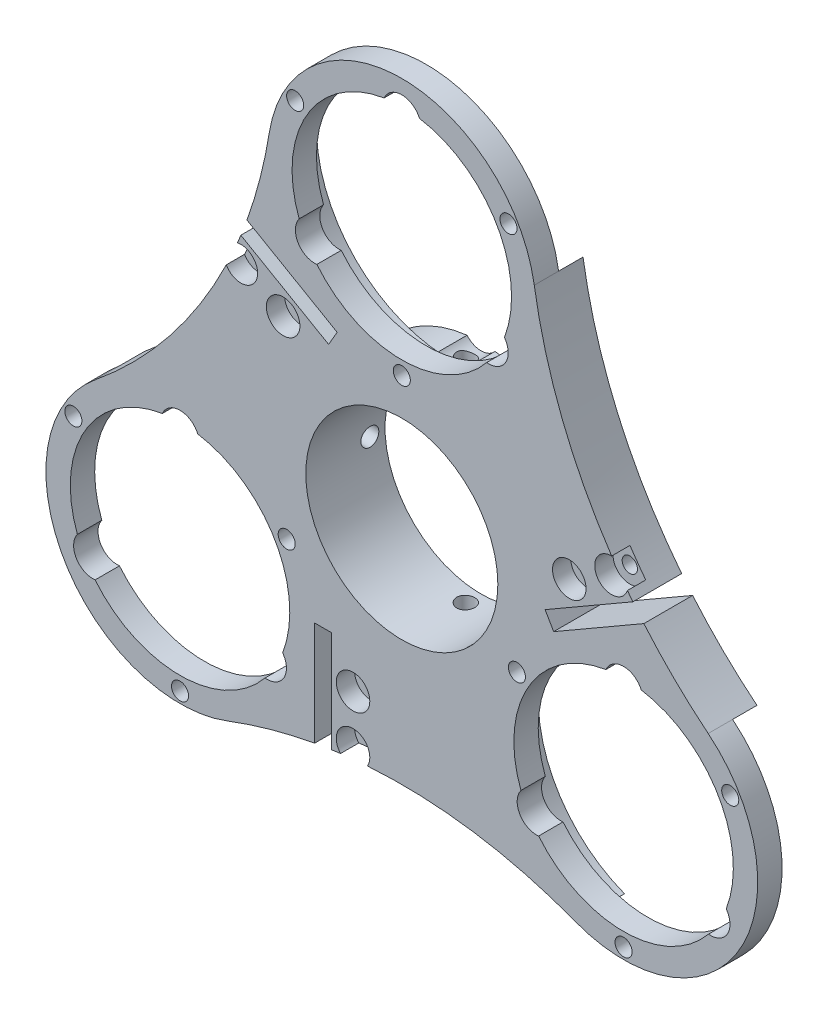
SolidWorks part; units mm, degrees
ref_plane "前视基准面" through (0, 0, 0) normal (0, 0, 1) x (1, 0, 0)
ref_plane "上视基准面" through (0, 0, 0) normal (0, 1, 0) x (1, 0, 0)
ref_plane "右视基准面" through (0, 0, 0) normal (1, 0, 0) x (0, 0, -1)
sketch "草图1" plane through (0, 0, 0) normal (0, 0, 1) x (1, 0, 0)
  circle A0 centre (0, 0) radius 15.75
  circle A1 centre (0, 0) radius 23 construction
  circle A3 centre (0, 0) radius 20
extrude "凸台-拉伸1" add sketch "草图1" along normal blind 5
sketch "草图2" plane through (0, 0, 5) normal (0, 0, 1) x (1, 0, 0)
  circle A0 centre (0, 0) radius 24 construction
  arc A2 (0, -25.8924) -> (22.4235, 12.9462) centre (20.7846, -12) ccw
  arc A3 (-22.4235, 12.9462) -> (0, -25.8924) centre (-20.7846, -12) ccw
  arc A5 (22.4235, 12.9462) -> (-22.4235, 12.9462) centre (0, 24) ccw
  point P12 (0, 0)
extrude "凸台-拉伸2" add sketch "草图2" along normal blind 8
sketch "草图3" plane through (0, 0, 13) normal (0, 0, 1) x (1, 0, 0)
  circle A0 centre (0, 42) radius 18
  circle A1 centre (36.3731, -21) radius 18
  circle A2 centre (-36.3731, -21) radius 18
  point P3 (0, 42)
  point P10 (0, 0)
  dimension "D1" = 3
  dimension "D3" = 42
extrude "凸台-拉伸3" add sketch "草图3" along normal blind 12
sketch "草图8" plane through (0, 0, 5) normal (0, 0, -1) x (-1, 0, 0)
  line L0 (0, 42) -> (36.3731, -21) construction
  line L1 (0, 0) -> (18.1865, 10.5) construction
  line L2 (18.1865, 10.5) -> (86.4245, 49.8972) construction
  line L3 (0, 0) -> (0, -8.0959) construction
  circle A0 centre (0, 0) radius 42 construction
  circle A4 centre (0, 42) radius 22
  circle A5 centre (36.3731, -21) radius 22
  circle A6 centre (-36.3731, -21) radius 22
  arc A7 (21.7226, 45.4827) -> (50.2505, -3.929) centre (100.7138, 58.1471) ccw
  arc A8 (-21.7226, 45.4827) -> (-50.2505, -3.929) centre (-100.7138, 58.1471) cw
  arc A9 (28.5279, -41.5537) -> (-28.5279, -41.5537) centre (0, -116.2943) ccw
  point P12 (0, 0)
  point P14 (0, 0)
  arc M7 (22.4235, 12.9462) -> (-22.4235, 12.9462) centre (0, 24) ccw
  arc M9 (-22.4235, 12.9462) -> (0, -25.8924) centre (-20.7846, -12) ccw
  arc M11 (0, -25.8924) -> (22.4235, 12.9462) centre (20.7846, -12) ccw
  dimension "D1" = 3
extrude "凸台-拉伸6" add sketch "草图8" against normal up to surface (8 mm away) contours A4 M7 | A7 A4 A5 M7 M11 | A5 M11 | A9 A5 A6 M11 M9 | A6 M9 | A4 A8 A6 M9 M7
sketch "草图4" plane through (0, 0, 25) normal (0, 0, 1) x (1, 0, 0)
  circle A0 centre (0, 42) radius 15
  circle A1 centre (36.3731, -21) radius 15
  circle A2 centre (-36.3731, -21) radius 15
  point P10 (0, 0)
  dimension "D1" = 3
extrude "切除-拉伸1" cut sketch "草图4" against normal blind 16
sketch "草图6" plane through (0, 0, 25) normal (0, 0, 1) x (1, 0, 0)
  arc A7 (2.6444, 56.7651) -> (-2.6444, 56.7651) centre (0, 58.5) ccw
  arc A11 (2.6444, 56.7651) -> (-2.6444, 56.7651) centre (0, 42) ccw
  arc A12 (11.4647, 32.3274) -> (14.1091, 36.9075) centre (14.2894, 33.75) ccw
  arc A13 (11.4647, 32.3274) -> (14.1091, 36.9075) centre (0, 42) ccw
  arc A14 (-14.1091, 36.9075) -> (-11.4647, 32.3274) centre (-14.2894, 33.75) ccw
  arc A15 (-14.1091, 36.9075) -> (-11.4647, 32.3274) centre (0, 42) ccw
  arc A16 (47.8378, -30.6726) -> (50.4822, -26.0925) centre (50.6625, -29.25) ccw
  arc A17 (47.8378, -30.6726) -> (50.4822, -26.0925) centre (36.3731, -21) ccw
  arc A18 (22.264, -26.0925) -> (24.9083, -30.6726) centre (22.0836, -29.25) ccw
  arc A19 (22.264, -26.0925) -> (24.9083, -30.6726) centre (36.3731, -21) ccw
  arc A20 (39.0174, -6.2349) -> (33.7287, -6.2349) centre (36.3731, -4.5) ccw
  arc A21 (39.0174, -6.2349) -> (33.7287, -6.2349) centre (36.3731, -21) ccw
  arc A22 (-50.4822, -26.0925) -> (-47.8378, -30.6726) centre (-50.6625, -29.25) ccw
  arc A23 (-50.4822, -26.0925) -> (-47.8378, -30.6726) centre (-36.3731, -21) ccw
  arc A24 (-33.7287, -6.2349) -> (-39.0174, -6.2349) centre (-36.3731, -4.5) ccw
  arc A25 (-33.7287, -6.2349) -> (-39.0174, -6.2349) centre (-36.3731, -21) ccw
  arc A26 (-24.9083, -30.6726) -> (-22.264, -26.0925) centre (-22.0836, -29.25) ccw
  arc A27 (-24.9083, -30.6726) -> (-22.264, -26.0925) centre (-36.3731, -21) ccw
  point P14 (0, 42)
  point P25 (36.3731, -21)
  point P37 (-36.3731, -21)
  point P38 (0, 0)
  dimension "D1" = 3
  dimension "D2" = 16.5
sketch "草图7" plane through (0, 0, 9) normal (0, 0, 1) x (1, 0, 0)
  circle A0 centre (0, 42) radius 2
  circle A1 centre (36.3731, -21) radius 2
  circle A2 centre (-36.3731, -21) radius 2
  point P3 (36.3731, -21)
  point P9 (0, 0)
  dimension "D1" = 3
extrude "切除-拉伸2" cut sketch "草图7" against normal blind 10
extrude "凸台-拉伸7" add sketch "草图6" against normal up to next
sketch "草图9" plane through (0, 0, 25) normal (0, 0, 1) x (1, 0, 0)
  circle A0 centre (0, 42) radius 17 construction
  circle A1 centre (0, 59) radius 1.475
  circle A2 centre (14.7224, 33.5) radius 1.475
  circle A3 centre (-14.7224, 33.5) radius 1.475
  circle A4 centre (51.0955, -29.5) radius 1.475
  circle A5 centre (21.6506, -29.5) radius 1.475
  circle A6 centre (36.3731, -4) radius 1.475
  circle A7 centre (36.3731, -21) radius 17 construction
  circle A8 centre (-51.0955, -29.5) radius 1.475
  circle A9 centre (-36.3731, -4) radius 1.475
  circle A10 centre (-21.6506, -29.5) radius 1.475
  circle A11 centre (-36.3731, -21) radius 17 construction
  point P12 (0, 42)
  point P21 (36.3731, -21)
  point P30 (-36.3731, -21)
  point P31 (0, 0)
  dimension "D1" = 3
  dimension "D2" = 3
ref_plane "基准面1" through (0, 0, 2.5) normal (0, 0, -1) x (-1, 0, 0)
sketch "草图10" plane through (0, 0, 2.5) normal (0, 0, -1) x (-1, 0, 0)
  line L0 (0, 26.5971) -> (0, -28.7314) construction
  line L1 (0, 23.6711) -> (1.475, 23.6711)
  line L2 (1.475, 23.6711) -> (1.475, -24.2093)
  line L3 (1.475, -24.2093) -> (0, -24.2093)
  line L4 (0, -24.2093) -> (0, 23.6711)
revolve "切除-旋转1" cut sketch "草图10" angle 360 about L0
sketch "草图11" plane through (0, 0, 2.5) normal (0, 0, -1) x (-1, 0, 0)
  line L0 (-35.3446, 0) -> (29.9106, 0) construction
  line L1 (-23.6643, 0) -> (-23.6643, 1.475)
  line L2 (-23.6643, 1.475) -> (24.1188, 1.475)
  line L3 (24.1188, 1.475) -> (24.1188, 0)
  line L4 (24.1188, 0) -> (-23.6643, 0)
revolve "切除-旋转2" cut sketch "草图11" angle 360 about L0
sketch "草图14" plane through (0, 0, 5) normal (0, 0, -1) x (-1, 0, 0)
  circle A0 centre (0, 0) radius 15.75
extrude "切除-拉伸6" cut sketch "草图14" against normal up to surface (8 mm away) up to face at (-36.3731, -21, 13)
sketch "草图16" plane through (0, 0, 13) normal (0, 0, 1) x (1, 0, 0)
  arc A0 (-2.8987, 59.7651) -> (-16.8343, 35.6278) centre (0, 42) ccw
  arc A1 (2.8987, 59.7651) -> (-2.8987, 59.7651) centre (0, 58.5) ccw
  arc A2 (13.9357, 30.6072) -> (16.8343, 35.6278) centre (14.2894, 33.75) ccw
  arc A3 (-16.8343, 35.6278) -> (-13.9357, 30.6072) centre (-14.2894, 33.75) ccw
  arc A4 (-13.9357, 30.6072) -> (13.9357, 30.6072) centre (0, 42) ccw
  arc A5 (16.8343, 35.6278) -> (2.8987, 59.7651) centre (0, 42) ccw
  arc A6 (53.2074, -27.3722) -> (39.2717, -3.2349) centre (36.3731, -21) ccw
  arc A7 (50.3087, -32.3928) -> (53.2074, -27.3722) centre (50.6625, -29.25) ccw
  arc A8 (19.5387, -27.3722) -> (22.4374, -32.3928) centre (22.0836, -29.25) ccw
  arc A9 (39.2717, -3.2349) -> (33.4744, -3.2349) centre (36.3731, -4.5) ccw
  arc A10 (33.4744, -3.2349) -> (19.5387, -27.3722) centre (36.3731, -21) ccw
  arc A11 (22.4374, -32.3928) -> (50.3087, -32.3928) centre (36.3731, -21) ccw
  arc A12 (-50.3087, -32.3928) -> (-22.4374, -32.3928) centre (-36.3731, -21) ccw
  arc A13 (-53.2074, -27.3722) -> (-50.3087, -32.3928) centre (-50.6625, -29.25) ccw
  arc A14 (-33.4744, -3.2349) -> (-39.2717, -3.2349) centre (-36.3731, -4.5) ccw
  arc A15 (-22.4374, -32.3928) -> (-19.5387, -27.3722) centre (-22.0836, -29.25) ccw
  arc A16 (-19.5387, -27.3722) -> (-33.4744, -3.2349) centre (-36.3731, -21) ccw
  arc A17 (-39.2717, -3.2349) -> (-53.2074, -27.3722) centre (-36.3731, -21) ccw
  point P12 (0, 42)
  point P24 (36.3731, -21)
  point P35 (-36.3731, -21)
  point P37 (0, 0)
  dimension "D1" = 3
  dimension "D2" = 3
extrude "切除-拉伸8" cut sketch "草图16" against normal mid plane 50
ref_plane "基准面2" through (0, 0, 9) normal (0, 0, -1) x (-1, 0, 0)
sketch "草图17" plane through (0, 0, 9) normal (0, 0, -1) x (-1, 0, 0)
  circle A0 centre (0, 42) radius 22
  circle A1 centre (36.3731, -21) radius 22
  circle A2 centre (-36.3731, -21) radius 22
extrude "切除-拉伸9" cut sketch "草图17" along normal up to surface (4 mm away) up to face at (0, 42, 5)
sketch "草图18" plane through (0, 0, 9) normal (0, 0, -1) x (-1, 0, 0)
  circle A0 centre (0, 42) radius 20.2 construction
  circle A1 centre (0, 21.8) radius 1.4
  circle A2 centre (-17.4937, 52.1) radius 1.4
  circle A3 centre (17.4937, 52.1) radius 1.4
  circle A4 centre (53.8668, -10.9) radius 1.4
  circle A5 centre (36.3731, -41.2) radius 1.4
  circle A6 centre (18.8794, -10.9) radius 1.4
  circle A7 centre (-36.3731, -41.2) radius 1.4
  circle A8 centre (-53.8668, -10.9) radius 1.4
  circle A9 centre (-18.8794, -10.9) radius 1.4
  point P12 (0, 42)
  point P24 (0, 0)
  dimension "D1" = 3
  dimension "D2" = 3
extrude "切除-拉伸10" cut sketch "草图18" against normal up to surface (4 mm away) up to face at (15.75, 0, 13)
sketch "草图19" plane through (0, 0, 0) normal (0, 0, -1) x (-1, 0, 0)
  circle A0 centre (0, 21.8) radius 3
  circle A1 centre (18.8794, -10.9) radius 3
  circle A2 centre (-18.8794, -10.9) radius 3
  point P10 (0, 0)
  dimension "D1" = 3
extrude "切除-拉伸11" cut sketch "草图19" against normal up to surface (5 mm away) up to face at (24.4698, 14.1276, 5)
sketch "草图20" plane through (0, 0, 5) normal (0, 0, -1) x (-1, 0, 0)
  line L0 (8, -51.1865) -> (8, 97.775) construction
  circle A0 centre (8, -35.0967) radius 1.25
  circle A1 centre (8, -27.0967) radius 1.25
  circle A6 centre (-27.4665, 6.6202) radius 1.25
  circle A7 centre (-34.3947, 10.6202) radius 1.25
  circle A8 centre (19.4665, 20.4766) radius 1.25
  circle A9 centre (26.3947, 24.4766) radius 1.25
  point P17 (0, 0)
  dimension "D2" = 8
  dimension "D3" = 3
  dimension "D1" = 8
extrude "切除-拉伸13" cut sketch "草图20" against normal blind 10
sketch "草图21" plane through (0, 0, 13) normal (0, 0, 1) x (1, 0, 0)
  circle A0 centre (-8, -35.0967) radius 2.75
  circle A1 centre (-8, -27.0967) radius 2.75
  circle A2 centre (-26.3947, 24.4766) radius 2.75
  circle A3 centre (-19.4665, 20.4766) radius 2.75
  circle A4 centre (34.3947, 10.6202) radius 2.75
  circle A5 centre (27.4665, 6.6202) radius 2.75
  point P16 (0, 0)
  dimension "D1" = 3
extrude "切除-拉伸14" cut sketch "草图21" against normal blind 3
sketch "草图22" plane through (0, 0, 13) normal (0, 0, 1) x (1, 0, 0)
  line L0 (-11.5, -63.5855) -> (-11.5, -45.8122) construction
  line L1 (-11.5, -20.5) -> (-11.5, -47.2246)
  line L2 (-11.5, -47.2246) -> (-14.3, -47.2246)
  line L3 (-14.3, -47.2246) -> (-14.3, -20.5)
  line L4 (-14.3, -20.5) -> (-11.5, -20.5)
  line L5 (-33.7477, 35.9965) -> (-10.6035, 22.6342)
  line L6 (-10.6035, 22.6342) -> (-12.0035, 20.2093)
  line L7 (-12.0035, 20.2093) -> (-35.1477, 33.5716)
  line L8 (-35.1477, 33.5716) -> (-33.7477, 35.9965)
  line L9 (48.0477, 11.2281) -> (24.9035, -2.1342)
  line L10 (24.9035, -2.1342) -> (23.5035, 0.2907)
  line L11 (23.5035, 0.2907) -> (46.6477, 13.653)
  line L12 (46.6477, 13.653) -> (48.0477, 11.2281)
  point P18 (0, 0)
  dimension "D1" = 11.5
  dimension "D2" = 2.8
  dimension "D3" = 20.5
  dimension "D4" = 3
extrude "切除-拉伸15" cut sketch "草图22" against normal blind 10
